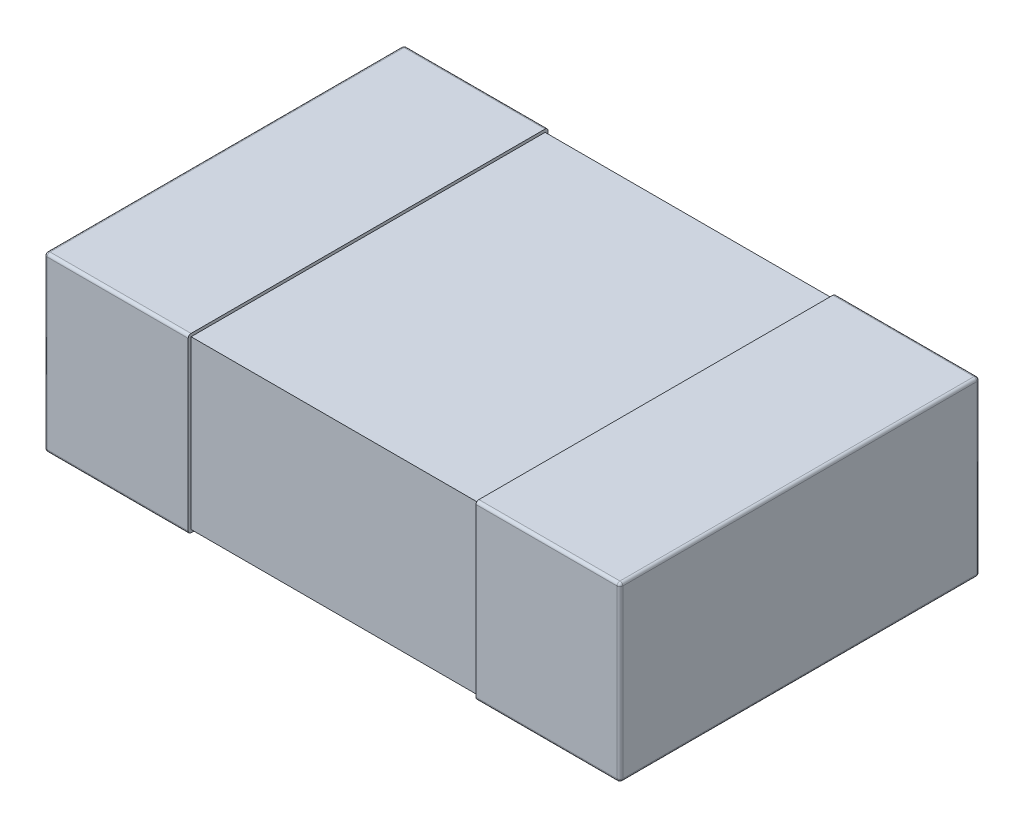
SolidWorks part; units mm, degrees
ref_plane "Front Plane" through (0, 0, 0) normal (0, 0, 1) x (1, 0, 0)
ref_plane "Top Plane" through (0, 0, 0) normal (0, 1, 0) x (1, 0, 0)
ref_plane "Right Plane" through (0, 0, 0) normal (1, 0, 0) x (0, 0, -1)
sketch "Sketch1" plane through (0, 0, 0) normal (0, 1, 0) x (1, 0, 0)
  line L0 (0, 0.15) -> (0, -0.15) construction
  line L1 (-1, 0) -> (0, 0) construction
  line L3 (-1, 0.625) -> (-0.5, 0.625)
  line L4 (-1, 0.625) -> (-1, -0.625)
  line L5 (-1, -0.625) -> (-0.5, -0.625)
  line L6 (-0.5, 0.625) -> (-0.5, -0.625)
  dimension "BANDWIDTH" = 0.5
  dimension "WIDTH" = 1.25
  dimension "LENGTH-HALF" = 1
extrude "THICKNESS" add sketch "Sketch1" along normal mid plane 0.6
fillet "Fillet1" radius 0.01 8 edges at (-1, -0.3, 0) (-0.75, -0.3, -0.625) (-1, 0, -0.625) (-0.75, -0.3, 0.625) (-1, 0, 0.625) (-1, 0.3, 0) (-0.75, 0.3, -0.625) (-0.75, 0.3, 0.625)
sketch "Sketch2" plane through (0, 0, 0) normal (1, 0, 0) x (0, 0, -1)
  line L0 (0, 0.3) -> (0, -0.3) construction
  line L1 (-0.615, 0.29) -> (0.615, 0.29)
  line L2 (-0.615, 0.29) -> (-0.615, -0.29)
  line L3 (-0.615, -0.29) -> (0.615, -0.29)
  line L4 (0.615, 0.29) -> (0.615, -0.29)
  line L5 (-0.615, 0.3) -> (0.615, 0.3) construction
  line L6 (-0.615, -0.3) -> (0.615, -0.3) construction
  line L7 (-0.625, 0) -> (0.625, 0) construction
  line L8 (-0.625, 0.29) -> (-0.625, -0.29) construction
  line L9 (0.625, 0.29) -> (0.625, -0.29) construction
  dimension "D1" = 0.01
  dimension "D2" = 0.01
extrude "Boss-Extrude2" add sketch "Sketch2" against normal up to surface (0.5 mm away) up to face at (-0.5, 0, 0)
mirror "Mirror3" about plane through (0, 0, 0) normal (1, 0, 0) of "Boss-Extrude2", "Fillet1", "THICKNESS"
